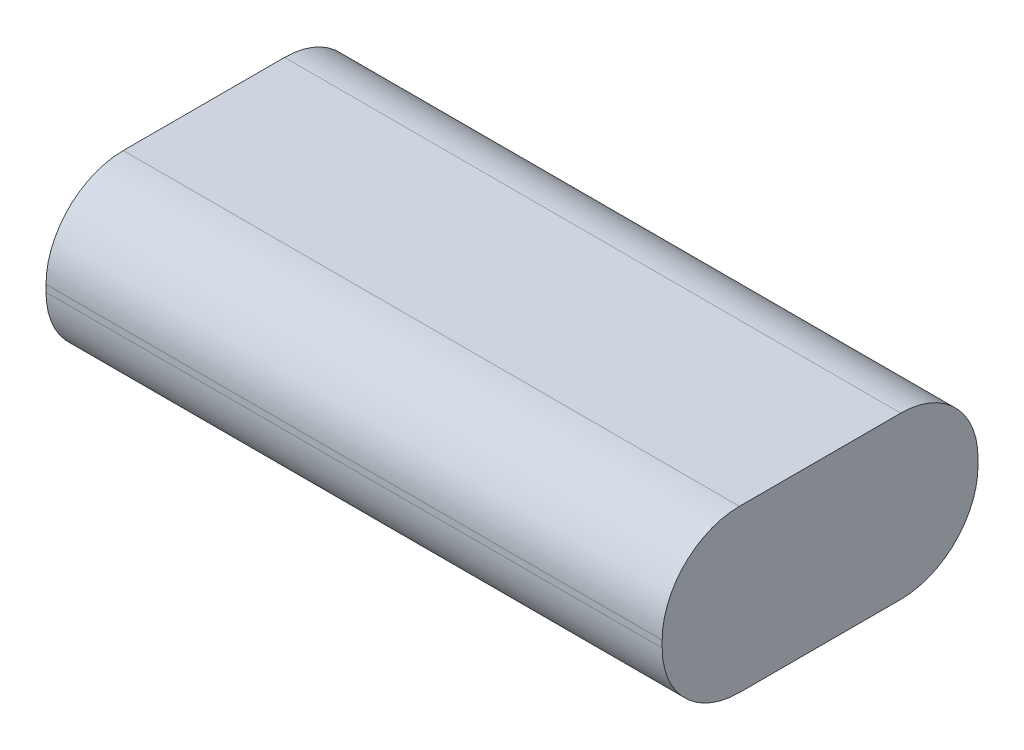
SolidWorks part; units mm, degrees
ref_plane "Front Plane" through (0, 0, 0) normal (0, 0, 1) x (1, 0, 0)
ref_plane "Top Plane" through (0, 0, 0) normal (0, 1, 0) x (1, 0, 0)
ref_plane "Right Plane" through (0, 0, 0) normal (1, 0, 0) x (0, 0, -1)
sketch "Sketch1" plane through (0, 0, 0) normal (0, 1, 0) x (1, 0, 0)
  line L1 (0, 0) -> (71.8, 0)
  line L2 (0, 0) -> (0, 36.8)
  line L3 (0, 36.8) -> (71.8, 36.8)
  line L4 (71.8, 0) -> (71.8, 36.8)
  dimension "D1" = 71.8
  dimension "D2" = 36.8
extrude "Boss-Extrude1" add sketch "Sketch1" along normal blind 18.8
fillet "Fillet1" radius 9 4 edges at (35.9, 18.8, -36.8) (35.9, 0, -36.8) (35.9, 0, 0) (35.9, 18.8, 0)
